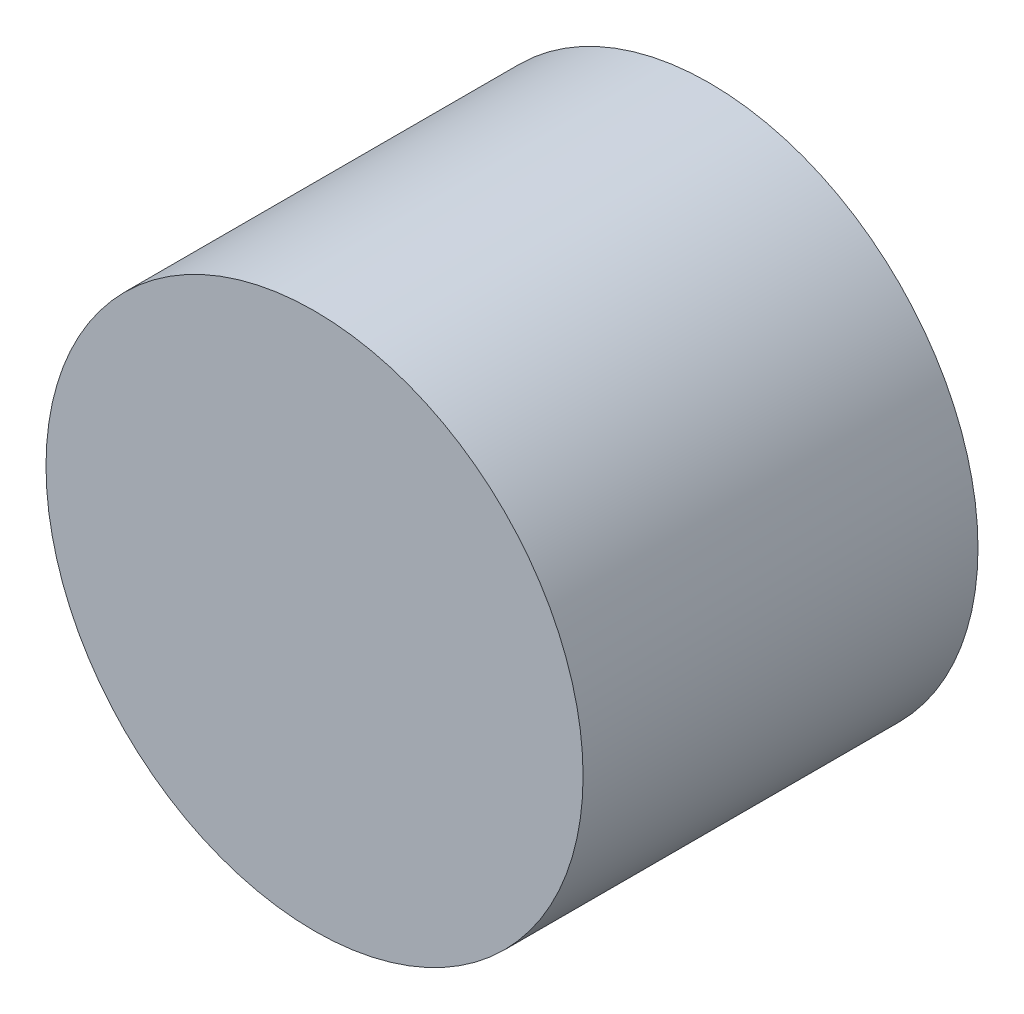
SolidWorks part; units mm, degrees
ref_plane "前视基准面" through (0, 0, 0) normal (0, 0, 1) x (1, 0, 0)
ref_plane "上视基准面" through (0, 0, 0) normal (0, 1, 0) x (1, 0, 0)
ref_plane "右视基准面" through (0, 0, 0) normal (1, 0, 0) x (0, 0, -1)
other "Configuration Table"
sketch "草图1" plane through (0, 0, 0) normal (0, 0, 1) x (1, 0, 0)
  circle A0 centre (0, 0) radius 17
  dimension "D1" = 34
extrude "凸台-拉伸1" add sketch "草图1" along normal blind 25
hole_wizard "M5 螺纹孔1" positions "草图5" profile "草图4" tap size "M5" standard "GB"
sketch "草图5" plane through (0, 0, 0) normal (0, 0, -1) x (-1, 0, 0)
  point P0 (0, 0)
sketch "草图4" plane through (0, 0, 0) normal (1, 0, 0) x (0, 1, 0)
  line L0 (0, 0) -> (0, 5.2618)
  line L1 (0, 5.2618) -> (2.1, 4)
  line L2 (2.1, 4) -> (2.1, 0)
  line L5 (2.1, 0) -> (0, 0)
  line L10 (0, 5.2618) -> (-2.1, 4) construction
  line L11 (0, -6.35) -> (0, 107.95) construction
  dimension "螺纹孔钻头直径" = 4.2
  dimension "螺纹孔钻头深度" = 4
  dimension "导头角度" = 118
cosmetic thread "孔螺纹线1"
